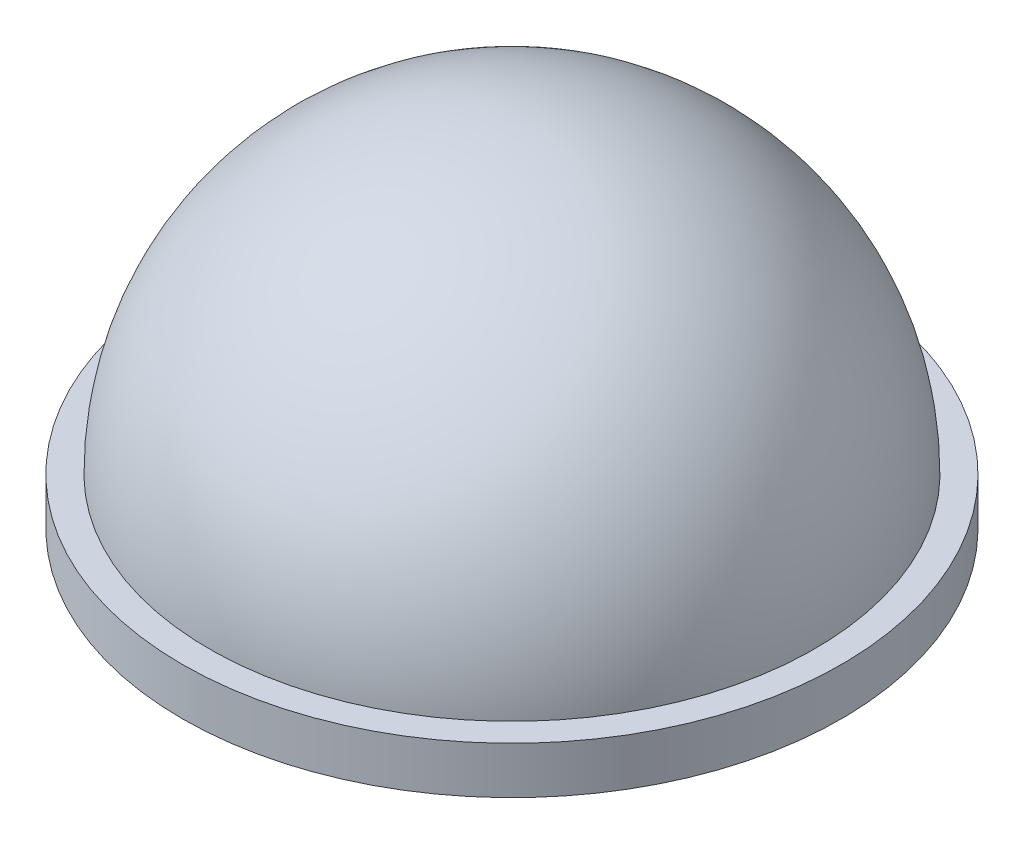
SolidWorks part; units mm, degrees
ref_plane "前视基准面" through (0, 0, 0) normal (0, 0, 1) x (1, 0, 0)
ref_plane "上视基准面" through (0, 0, 0) normal (0, 1, 0) x (1, 0, 0)
ref_plane "右视基准面" through (0, 0, 0) normal (1, 0, 0) x (0, 0, -1)
other "Configuration Table"
sketch "草图1" plane through (0, 0, 0) normal (0, 1, 0) x (1, 0, 0)
  circle A0 centre (0, 0) radius 4.9
  dimension "D1" = 9.8
extrude "凸台-拉伸1" add sketch "草图1" along normal blind 0.7
sketch "草图2" plane through (0, 0, 0) normal (0, 0, 1) x (1, 0, 0)
  line L0 (4.9, 0.7) -> (-4.9, 0.7) construction
  line L1 (-4.5, 0.7) -> (0, 0.7)
  line L2 (0, 0.7) -> (0, 5.2)
  circle A0 centre (0, 0.7) radius 4.5
  dimension "D1" = 9
revolve "旋转1" add sketch "草图2" angle 360 about L2
